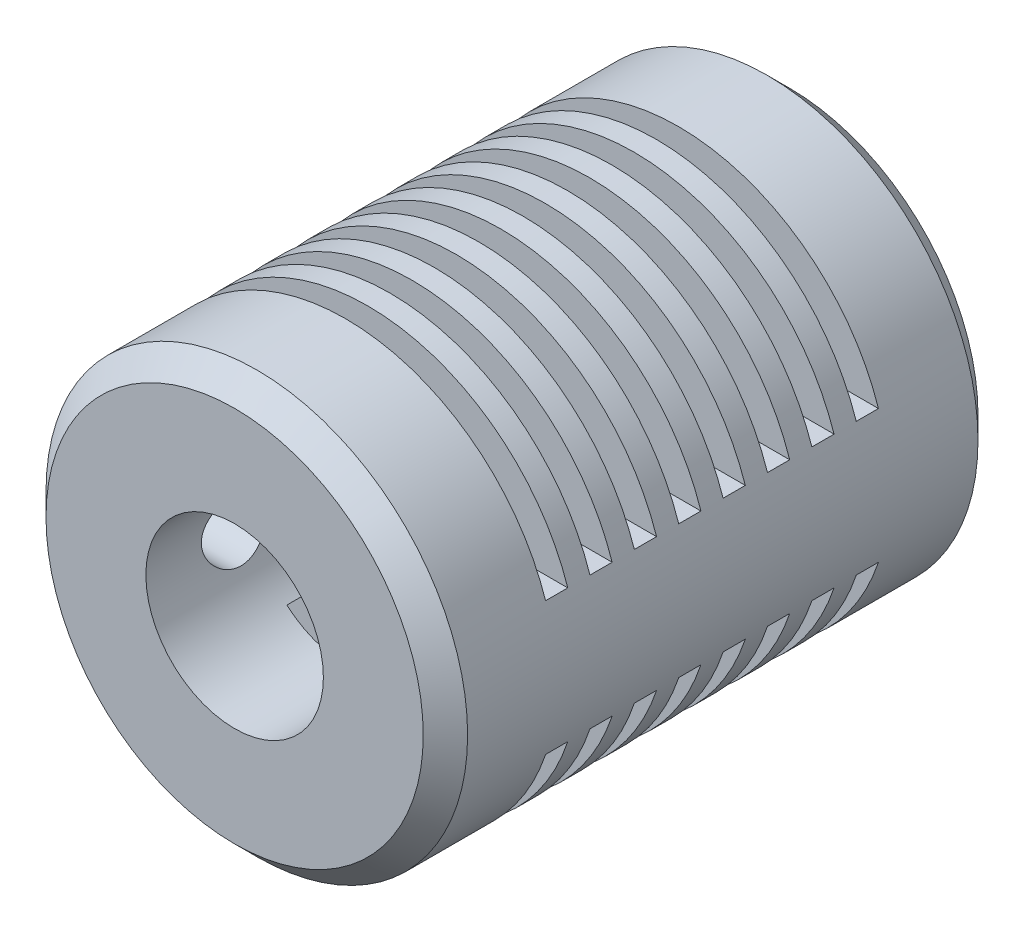
SolidWorks part; units mm, degrees
ref_plane "Alzado" through (0, 0, 0) normal (0, 0, 1) x (1, 0, 0)
ref_plane "Planta" through (0, 0, 0) normal (0, 1, 0) x (1, 0, 0)
ref_plane "Vista lateral" through (0, 0, 0) normal (1, 0, 0) x (0, 0, -1)
sketch "Croquis1" plane through (0, 0, 0) normal (0, 0, 1) x (1, 0, 0)
  circle A0 centre (0, 0) radius 9.5
  dimension "D1" = 19
extrude "Saliente-Extruir1" add sketch "Croquis1" along normal blind 25
sketch "Croquis2" plane through (0, 0, 25) normal (0, 0, 1) x (1, 0, 0)
  circle A0 centre (0, 0) radius 2.5
  dimension "D1" = 5
extrude "Cortar-Extruir1" cut sketch "Croquis2" against normal through all
sketch "Croquis3" plane through (0, 0, 25) normal (0, 0, 1) x (1, 0, 0)
  circle A0 centre (0, 0) radius 4
  dimension "D1" = 8
extrude "Cortar-Extruir2" cut sketch "Croquis3" against normal blind 17
chamfer "Chaflán1" distance 1 angle 45 2 edges at (9.5, 0, 0) (9.5, 0, 25)
sketch "Croquis4" plane through (0, 0, 0) normal (1, 0, 0) x (0, 0, -1)
  line L0 (0, 0) -> (-25, 0) construction
  line L1 (-25, 8.5) -> (-25, -8.5) construction
  circle A0 centre (-21, 0) radius 1.5
  circle A1 centre (-4, 0) radius 1.5
  dimension "D1" = 3
  dimension "D2" = 3
  dimension "D3" = 4
  dimension "D4" = 4
extrude "Cortar-Extruir3" cut sketch "Croquis4" against normal through all
sketch "Croquis5" plane through (0, 0, 0) normal (1, 0, 0) x (0, 0, -1)
  line L0 (-18, 11) -> (-17, 11)
  line L1 (0, -8.5) -> (0, 8.5) construction
  line L2 (-25, 8.5) -> (-25, -8.5) construction
  line L3 (0, 3) -> (-25, 3) construction
  line L4 (-18, 3) -> (-18, 11)
  line L5 (-20, 3) -> (-19, 3)
  line L6 (-20, 3) -> (-20, 11)
  line L7 (-20, 11) -> (-19, 11)
  line L8 (-19, 3) -> (-19, 11)
  line L9 (-17, 3) -> (-17, 11)
  line L10 (-18, 3) -> (-17, 3)
  line L11 (-16, 11) -> (-15, 11)
  line L12 (-16, 3) -> (-16, 11)
  line L13 (-15, 3) -> (-15, 11)
  line L14 (-16, 3) -> (-15, 3)
  line L15 (-14, 11) -> (-13, 11)
  line L16 (-14, 3) -> (-14, 11)
  line L17 (-13, 3) -> (-13, 11)
  line L18 (-14, 3) -> (-13, 3)
  line L19 (-12, 11) -> (-11, 11)
  line L20 (-12, 3) -> (-12, 11)
  line L21 (-11, 3) -> (-11, 11)
  line L22 (-12, 3) -> (-11, 3)
  line L23 (-10, 11) -> (-9, 11)
  line L24 (-10, 3) -> (-10, 11)
  line L25 (-9, 3) -> (-9, 11)
  line L26 (-10, 3) -> (-9, 3)
  line L27 (-8, 11) -> (-7, 11)
  line L28 (-8, 3) -> (-8, 11)
  line L29 (-7, 3) -> (-7, 11)
  line L30 (-8, 3) -> (-7, 3)
  line L31 (-6, 11) -> (-5, 11)
  line L32 (-6, 3) -> (-6, 11)
  line L33 (-5, 3) -> (-5, 11)
  line L34 (-6, 3) -> (-5, 3)
  line L35 (-18, -3) -> (-17, -3)
  line L36 (-18, -11) -> (-18, -3)
  line L37 (-17, -11) -> (-17, -3)
  line L38 (-18, -11) -> (-17, -11)
  line L39 (-16, -3) -> (-15, -3)
  line L40 (-16, -11) -> (-16, -3)
  line L41 (-15, -11) -> (-15, -3)
  line L42 (-16, -11) -> (-15, -11)
  line L43 (-14, -3) -> (-13, -3)
  line L44 (-14, -11) -> (-14, -3)
  line L45 (-13, -11) -> (-13, -3)
  line L46 (-14, -11) -> (-13, -11)
  line L47 (-12, -3) -> (-11, -3)
  line L48 (-12, -11) -> (-12, -3)
  line L49 (-11, -11) -> (-11, -3)
  line L50 (-12, -11) -> (-11, -11)
  line L51 (-10, -3) -> (-9, -3)
  line L52 (-10, -11) -> (-10, -3)
  line L53 (-9, -11) -> (-9, -3)
  line L54 (-10, -11) -> (-9, -11)
  line L55 (-8, -3) -> (-7, -3)
  line L56 (-8, -11) -> (-8, -3)
  line L57 (-7, -11) -> (-7, -3)
  line L58 (-8, -11) -> (-7, -11)
  line L59 (-6, -3) -> (-5, -3)
  line L60 (-6, -11) -> (-6, -3)
  line L61 (-5, -11) -> (-5, -3)
  line L62 (-6, -11) -> (-5, -11)
  line L63 (-20, -3) -> (-19, -3)
  line L64 (-20, -11) -> (-20, -3)
  line L65 (-19, -11) -> (-19, -3)
  line L66 (-20, -11) -> (-19, -11)
  dimension "D1" = 3
  dimension "D2" = 1
  dimension "D3" = 8
  dimension "D4" = 20
  dimension "D5" = 8
  dimension "D6" = 2
extrude "Cortar-Extruir4" cut sketch "Croquis5" against normal through all and the other way through all
